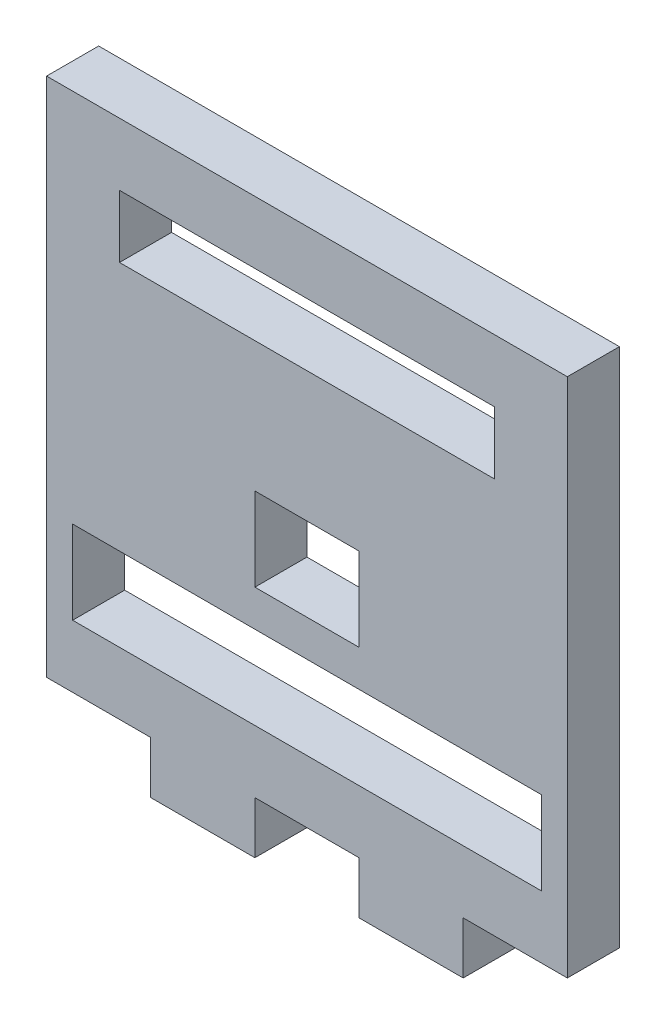
SolidWorks part; units mm, degrees
ref_plane "Front Plane" through (0, 0, 0) normal (0, 0, 1) x (1, 0, 0)
ref_plane "Top Plane" through (0, 0, 0) normal (0, 1, 0) x (1, 0, 0)
ref_plane "Right Plane" through (0, 0, 0) normal (1, 0, 0) x (0, 0, -1)
sketch "Esquisse1" plane through (0, 0, 0) normal (0, 0, 1) x (1, 0, 0)
  line L1 (0, 0) -> (-50, 0)
  line L2 (0, 0) -> (0, 50)
  line L3 (0, 50) -> (-50, 50)
  line L4 (-50, 0) -> (-50, 50)
  line L5 (-25, 50) -> (-25, 0) construction
  line L6 (0, 25) -> (-50, 25) construction
  line L7 (-43, 44) -> (-7, 44)
  line L8 (-43, 44) -> (-43, 38)
  line L9 (-43, 38) -> (-7, 38)
  line L10 (-7, 44) -> (-7, 38)
  line L11 (-25, 38) -> (-25, 44) construction
  line L12 (-43, 41) -> (-7, 41) construction
  line L13 (-30, 25.5) -> (-20, 25.5)
  line L14 (-30, 25.5) -> (-30, 17.5)
  line L15 (-30, 17.5) -> (-20, 17.5)
  line L16 (-20, 25.5) -> (-20, 17.5)
  line L17 (-25, 17.5) -> (-25, 25.5) construction
  line L18 (-30, 21.5) -> (-20, 21.5) construction
  line L19 (-47.5, 14) -> (-2.5, 14)
  line L20 (-47.5, 14) -> (-47.5, 6)
  line L21 (-47.5, 6) -> (-2.5, 6)
  line L22 (-2.5, 14) -> (-2.5, 6)
  line L23 (-25, 6) -> (-25, 14) construction
  line L24 (-47.5, 10) -> (-2.5, 10) construction
  point P22 (0, 0)
  point P60 (-25, 21.5)
  point P109 (-25, 10)
  point P192 (-25, 25)
  point P198 (-25, 41)
  dimension "D1" = 50
  dimension "D2" = 50
  dimension "D3" = 36
  dimension "D4" = 6
  dimension "D5" = 6
  dimension "D6" = 7
  dimension "D7" = 10
  dimension "D8" = 8
  dimension "D9" = 12.5
  dimension "D10" = 3.5
  dimension "D11" = 45
  dimension "D12" = 8
extrude "Boss.-Extru.1" add sketch "Esquisse1" along normal blind 5
sketch "Esquisse11" plane through (0, 0, 5) normal (0, 0, 1) x (1, 0, 0)
  line L0 (-50, 0) -> (0, 0) construction
  line L1 (-40, 0) -> (-30, 0)
  line L2 (-40, 0) -> (-40, -5)
  line L3 (-40, -5) -> (-30, -5)
  line L4 (-30, 0) -> (-30, -5)
  line L5 (-35, -5) -> (-35, 0) construction
  line L6 (-40, -2.5) -> (-30, -2.5) construction
  line L7 (0, -5) -> (-10, -5) construction
  line L8 (0, 0) -> (0, -5) construction
  line L9 (-20, 0) -> (-10, 0)
  line L10 (-20, 0) -> (-20, -5)
  line L11 (-20, -5) -> (-10, -5)
  line L12 (-10, 0) -> (-10, -5)
  line L13 (-15, -5) -> (-15, 0) construction
  line L14 (-20, -2.5) -> (-10, -2.5) construction
  point P112 (-35, -2.5)
  point P113 (-15, -2.5)
  dimension "D1" = 10
  dimension "D2" = 10
  dimension "D3" = 10
  dimension "D4" = 10
extrude "Boss.-Extru.2" add sketch "Esquisse11" against normal blind 5
